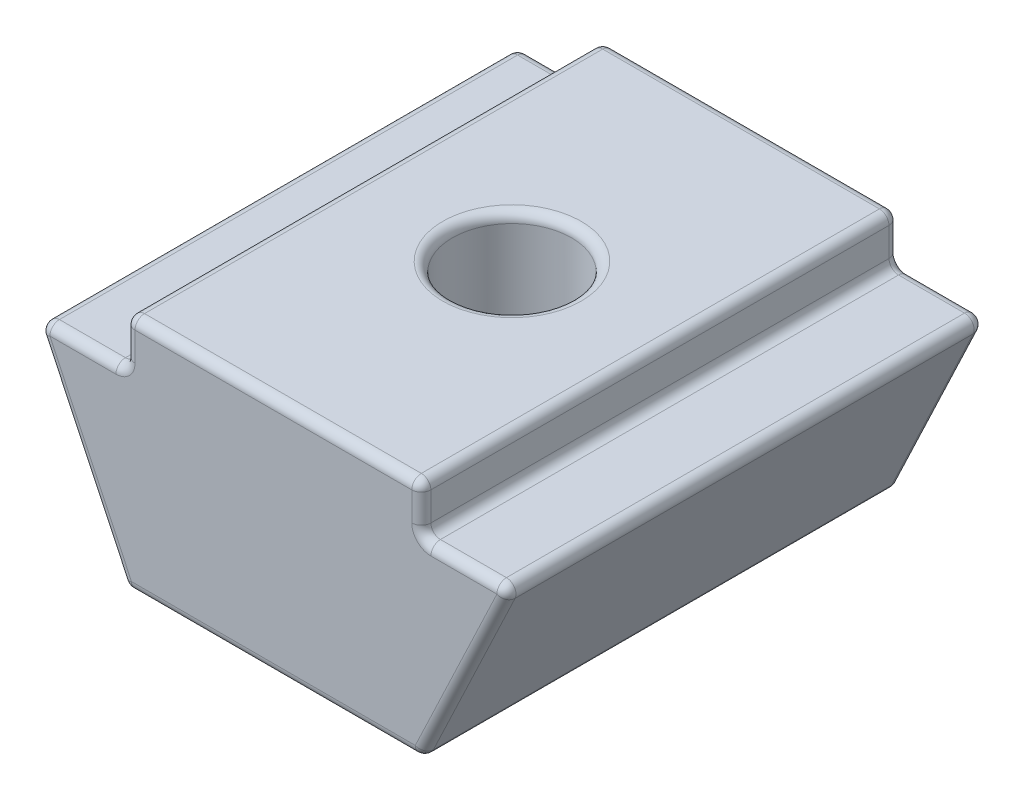
SolidWorks part; units mm, degrees
ref_plane "Front Plane" through (0, 0, 0) normal (0, 0, 1) x (1, 0, 0)
ref_plane "Top Plane" through (0, 0, 0) normal (0, 1, 0) x (1, 0, 0)
ref_plane "Right Plane" through (0, 0, 0) normal (1, 0, 0) x (0, 0, -1)
ref_plane "Rear Plane" through (0, 0, 10) normal (0, 0, 1) x (1, 0, 0)
sketch "MainSketch" plane through (0, 0, 0) normal (0, 0, 1) x (1, 0, 0)
  line L0 (-3.1, 0) -> (3.1, 0)
  line L1 (3.1, 0) -> (5, 4)
  line L2 (5, 4) -> (3.1, 4)
  line L3 (3.1, 4) -> (3.1, 5)
  line L4 (3.1, 5) -> (-3.1, 5)
  line L5 (-3.1, 5) -> (-3.1, 4)
  line L6 (-3.1, 4) -> (-5, 4)
  line L7 (-5, 4) -> (-3.1, 0)
  point P4 (0, 0)
  dimension "D1" = 4
  dimension "D2" = 5
  dimension "D3" = 6.2
  dimension "D4" = 10
extrude "NutExtrusion" add sketch "MainSketch" along normal up to surface (10 mm away) up to plane "Rear Plane"
sketch "HoleLocationSketch" plane through (0, 5, 0) normal (0, 1, 0) x (1, 0, 0)
  line L0 (-3.1, -10) -> (3.1, 0) construction
  line L1 (3.1, 0) -> (-3.1, 0) construction
  line L2 (3.1, -10) -> (3.1, 0) construction
  point P5 (0, -5)
hole_wizard "M3x0.5 Tapped Hole1" positions "Sketch3" profile "Sketch4" tap size "M3x0.5" standard "ANSI Metric" end condition through all
sketch "Sketch3" plane through (0, 5, 0) normal (0, 1, 0) x (1, 0, 0)
  point P0 (0, -5)
sketch "Sketch4" plane through (0, 5, 5) normal (1, 0, 0) x (0, 0, 1)
  line L0 (0, 0) -> (0, 5)
  line L1 (0, 5) -> (1.25, 5)
  line L2 (1.25, 5) -> (1.25, 0)
  line L5 (1.25, 0) -> (0, 0)
  line L11 (0, -6.35) -> (0, 107.95) construction
  dimension "Thru Tap Drill Dia." = 2.5
  dimension "Thru Tap Drill Depth" = 5
cosmetic thread "Hole Thread1" parameters "D2"=3
fillet "Cosmetic Fillets" radius 0.2 26 edges at (5, 4, 5) (3.1, 0, 5) (-3.1, 0, 5) (0, 0, 6.25) (4.05, 4, 0) (-3.1, 4.5, 0) (-4.05, 2, 0) (0, 0, 0) (4.05, 2, 0) (-5, 4, 5) (-4.05, 4, 0) (-3.1, 4, 5) (0, 5, 6.25) (-3.1, 5, 5) (0, 5, 0) (3.1, 5, 5) (3.1, 4.5, 0) (3.1, 4, 5) (-4.05, 2, 10) (-4.05, 4, 10) (-3.1, 4.5, 10) (0, 5, 10) (3.1, 4.5, 10) (4.05, 4, 10) (4.05, 2, 10) (0, 0, 10)
